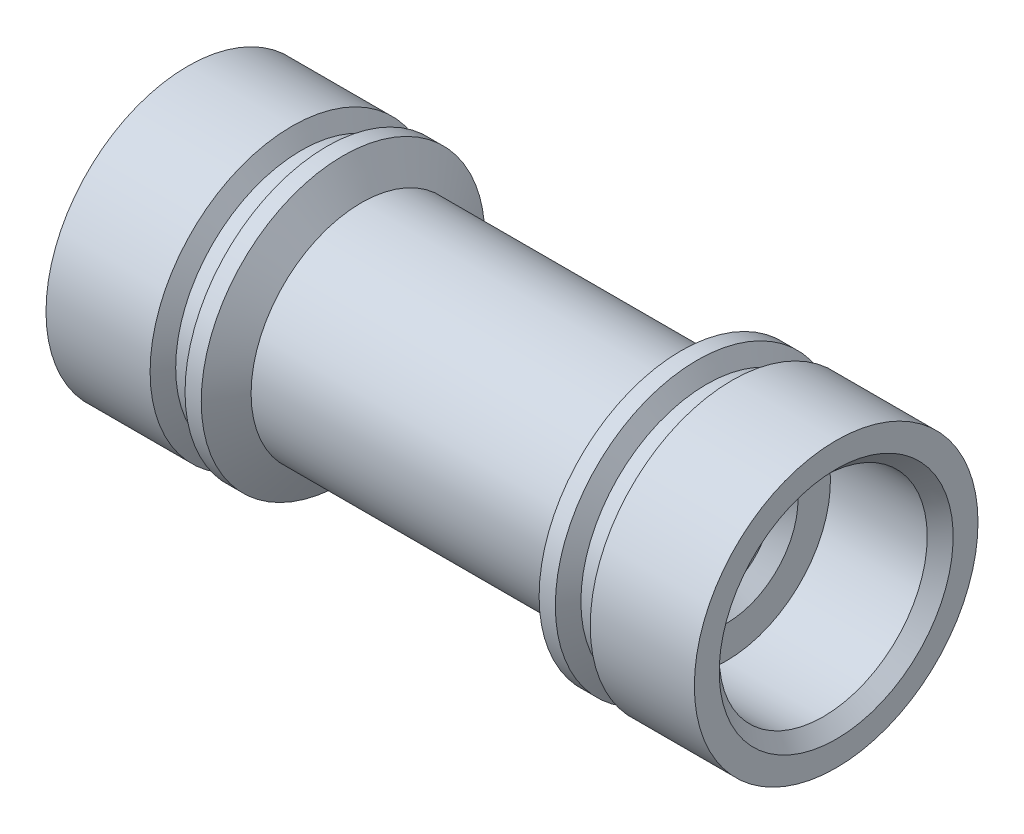
SolidWorks part; units mm, degrees
ref_plane "Front Plane" through (0, 0, 0) normal (0, 0, 1) x (1, 0, 0)
ref_plane "Top Plane" through (0, 0, 0) normal (0, 1, 0) x (1, 0, 0)
ref_plane "Right Plane" through (0, 0, 0) normal (1, 0, 0) x (0, 0, -1)
sketch "Sketch2" plane through (0, 0, 0) normal (0, 0, 1) x (1, 0, 0)
  line L0 (0, 0) -> (0, 28.4375) construction
  line L1 (-12.7, 4.075) -> (-8.4, 4.075) construction
  line L2 (-12.7, 4.075) -> (-12.7, -4.075) construction
  line L3 (-12.7, -4.075) -> (-8.4, -4.075) construction
  line L4 (-8.4, 4.075) -> (-8.4, -4.075) construction
  line L5 (-12.7, 4.075) -> (-8.4, -4.075) construction
  line L6 (-12.7, -4.075) -> (-8.4, 4.075) construction
  line L7 (8.4, 4.5) -> (55.1832, 4.5) construction
  line L8 (8.4, 4.5) -> (8.4, -4.5) construction
  line L9 (8.4, -4.5) -> (55.1832, -4.5) construction
  line L10 (55.1832, 4.5) -> (55.1832, -4.5) construction
  line L11 (8.4, 4.5) -> (55.1832, -4.5) construction
  line L12 (8.4, -4.5) -> (55.1832, 4.5) construction
  line L13 (-12.7, 0) -> (55.1832, 0) construction
  line L14 (-12.7, 5.5562) -> (-8.6216, 5.5562)
  line L21 (-5.9035, 4.318) -> (0, 4.318)
  line L22 (-12.7, 5.5562) -> (-12.7, 4.075)
  line L23 (-12.7, 4.075) -> (-8.4, 4.075)
  line L24 (-8.4, 4.075) -> (-8.4, 0)
  line L25 (-8.4, 0) -> (0, 0)
  line L26 (0, 0) -> (0, 4.318)
  line L27 (-33.5594, -5.5562) -> (-33.5594, 5.5562) construction
  line L28 (-8.6216, 5.5562) -> (-8.255, 4.9212)
  line L29 (-8.255, 4.9212) -> (-7.62, 4.9212)
  line L30 (-12.7, 5.5562) -> (12.7, 5.5562) construction
  line L31 (0, 1.6) -> (-12.5, 1.6)
  line L32 (-12.5, 1.6) -> (-14.1, 0)
  line L33 (-12.5, 1.6) -> (-12.5, -1.6) construction
  line L34 (-12.5, 1.6) -> (12.5, 1.6) construction
  line L35 (-8.4, 1.905) -> (-2.748, 1.905)
  line L36 (-2.748, 1.905) -> (-2.748, 0)
  line L37 (-8.4, 2.805) -> (-7.892, 2.297)
  line L38 (-2.748, 1.905) -> (-15.748, 1.905) construction
  line L39 (-2.748, 1.905) -> (-2.748, -1.905) construction
  line L40 (-2.748, -1.905) -> (-15.748, -1.905) construction
  line L41 (-15.748, 1.905) -> (-15.748, -1.905) construction
  line L42 (-7.892, 2.297) -> (-7.892, 0)
  line L46 (-7.62, 4.9212) -> (-7.2534, 5.5562)
  line L47 (-7.2534, 5.5562) -> (-6.6184, 5.5562)
  line L48 (-6.6184, 5.5562) -> (-5.9035, 4.318)
  line L49 (-7.9375, 4.9212) -> (-7.9375, 6.3987) construction
  line L50 (-7.9375, 6.3987) -> (7.9375, 6.3987) construction
  line L51 (-2.748, 1.905) -> (-0.843, 0)
  point P0 (-10.55, 0)
  point P5 (31.7916, 0)
  point P27 (-33.5594, 0)
  point P29 (-12.5, 0)
  point P33 (0, 6.3987)
  point P36 (0, 1.6)
  point P48 (-2.748, 0)
  point P51 (0, 5.5562)
  dimension "D3" = 4.318
  dimension "D4" = 11.1125
  dimension "D5" = 8.15
  dimension "D13" = 45
  dimension "D14" = 25
  dimension "D15" = 3.2
  dimension "D16" = 3.81
  dimension "D17" = 3.048
  dimension "D18" = 1.27
  dimension "D19" = 0.508
  dimension "D20" = 45
  dimension "D21" = 13
  dimension "D11" = 25.4
  dimension "D6" = 60
  dimension "D7" = 0.635
  dimension "D8" = 60
  dimension "D9" = 15.875
  dimension "D10" = 0.635
  dimension "D12" = 0.635
  dimension "D22" = 4.3
  dimension "D23" = 45
revolve "Revolve1" add sketch "Sketch2" angle 360 about L13
chamfer "Chamfer1" distance 0.508 angle 45 1 edges at (-12.7, -4.075, 0)
mirror "Mirror1" about plane through (0, 0, 0) normal (1, 0, 0) of bodies 101
equation "\"D22@Sketch2\"=4.3mm"
